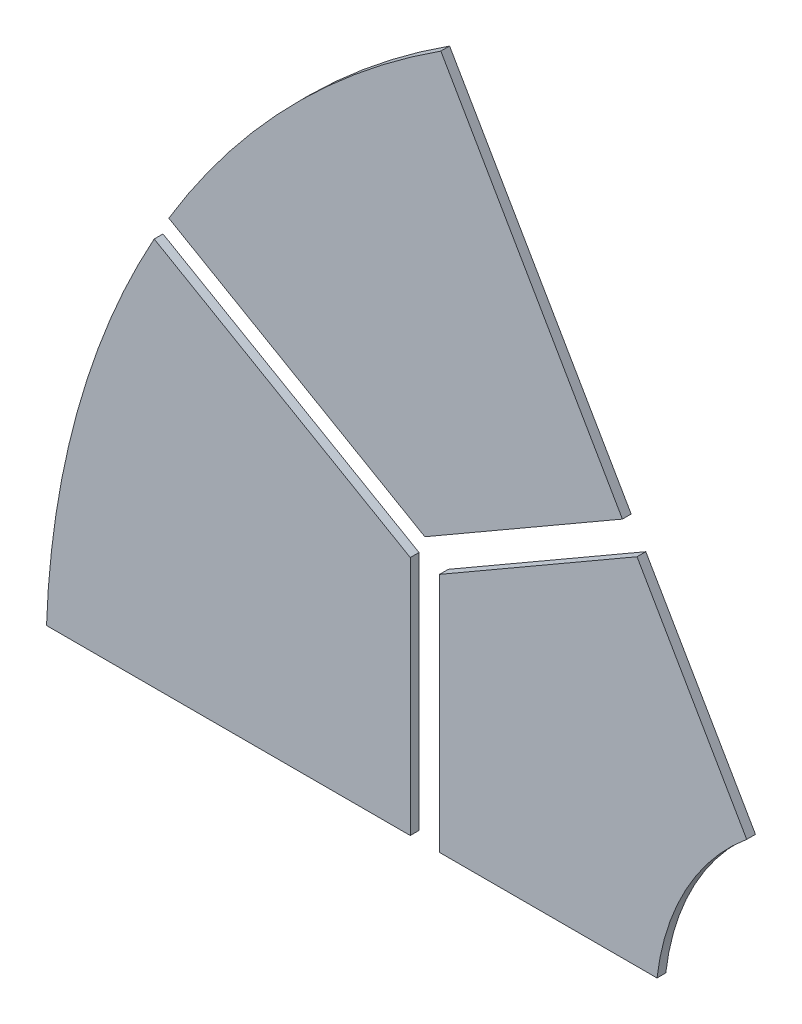
SolidWorks part; units mm, degrees
ref_plane "Front Plane" through (0, 0, 0) normal (0, 0, 1) x (1, 0, 0)
ref_plane "Top Plane" through (0, 0, 0) normal (0, 1, 0) x (1, 0, 0)
ref_plane "Right Plane" through (0, 0, 0) normal (1, 0, 0) x (0, 0, -1)
sketch "Sketch1" plane through (0, 0, 0) normal (0, 0, 1) x (1, 0, 0)
  line L0 (0, 0) -> (-10, 0)
  line L2 (-10, 0) -> (-15, 8.6603)
  line L4 (-340.2, 20) -> (-589.2607, 20)
  line L5 (-194.9205, 280.2917) -> (-319.272, 495.6748)
  line L6 (0, 0) -> (-15, 8.6603)
  line L7 (-109.821, 132.8951) -> (-184.9205, 262.9712)
  line L8 (-83.5769, 127.4389) -> (-312.2692, 523.5457)
  line L9 (-152.4, 0) -> (-609.6, 0)
  line L10 (-171.236, 20) -> (-589.2607, 20) construction
  line L11 (-171.236, 20) -> (-320.2, 20)
  line L13 (-320.2, 20) -> (-320.2, 173.3206)
  line L14 (-310.2, 190.6411) -> (-184.9205, 262.9712)
  line L16 (-340.2, 20) -> (-340.2, 184.8676)
  line L17 (-330.2, 202.1881) -> (-194.9205, 280.2917)
  line L18 (-532.858, 296.0987) -> (-532.9291, 296.1397)
  line L19 (-522.858, 313.4192) -> (-522.9291, 313.4603)
  line L20 (-320.2, 173.3206) -> (-320.2, 184.8676)
  line L21 (-109.821, 132.8951) -> (-319.272, 495.6748) construction
  line L22 (-330.2, 202.1881) -> (-505.5351, 303.4178)
  line L23 (-320.2, 184.8676) -> (-310.2, 190.6411)
  line L24 (-340.2, 184.8676) -> (-515.5351, 286.0973)
  arc A0 (-609.6, 0) -> (-312.2692, 523.5457) centre (0, 0) cw
  arc A1 (-83.5769, 127.4389) -> (-152.4, 0) centre (0, 0) ccw
  arc A2 (-589.2607, 20) -> (-515.5351, 286.0973) centre (0, 0) cw
  arc A3 (-109.821, 132.8951) -> (-144.0514, 94.7151) centre (0, 0) ccw
  arc A4 (-505.5351, 303.4178) -> (-319.272, 495.6748) centre (0, 0) cw
  arc A5 (-154.0514, 77.3946) -> (-171.236, 20) centre (0, 0) ccw
  arc A6 (-589.2607, 20) -> (-319.272, 495.6748) centre (0, 0) cw construction
  arc A7 (-154.0514, 77.3946) -> (-144.0514, 94.7151) centre (0, 0) cw
  arc A8 (-109.821, 132.8951) -> (-171.236, 20) centre (0, 0) ccw construction
  point P3 (-172.6, 281.6315)
  point P6 (0, 0)
  point P7 (-330.2, 0)
  point P10 (-165.1, 285.9616)
  point P11 (-527.9291, 304.8)
  point P12 (-330.2, 0)
  point P13 (-330.2, 190.6411)
  point P16 (-131.9823, 76.2)
  point P22 (-126.9823, 84.8603)
  point P24 (-320.2, 0)
  point P25 (-320.2, 184.8676)
  point P26 (-167.6, 272.9712)
  point P27 (-136.9823, 67.5397)
  point P29 (-340.2, 0)
  point P30 (-340.2, 196.4146)
  point P31 (-177.6, 290.2917)
  dimension "D4" = 330.2
  dimension "D3" = 330.2
  dimension "D1" = 20
extrude "Boss-Extrude1" add sketch "Sketch1" along normal blind 6 contours A2 L4 L16 L24 | A4 L22 L17 L5 | A5 A7 A3 L7 L14 L23 L20 L13 L11
